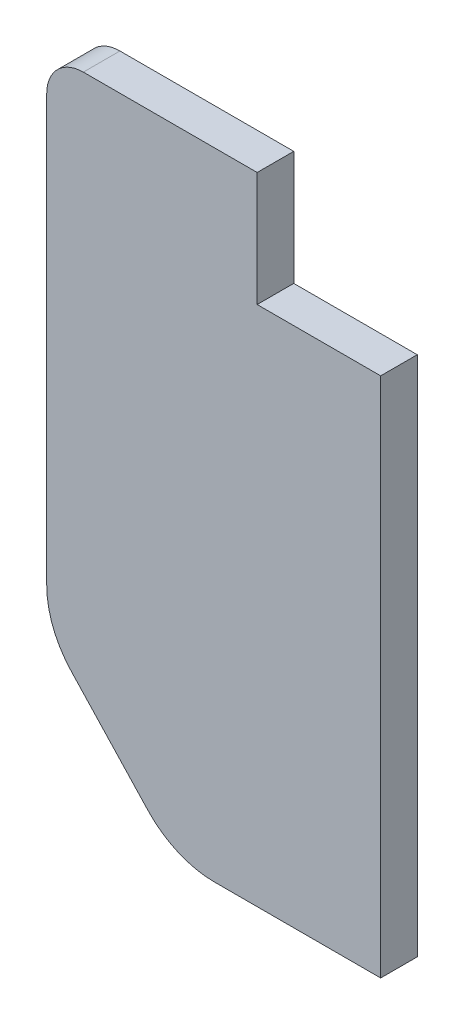
SolidWorks part; units mm, degrees
material "Q355"
ref_plane "前视基准面" through (0, 0, 0) normal (0, 0, 1) x (1, 0, 0)
ref_plane "上视基准面" through (0, 0, 0) normal (0, 1, 0) x (1, 0, 0)
ref_plane "右视基准面" through (0, 0, 0) normal (1, 0, 0) x (0, 0, -1)
sketch "草图1" plane through (0, 0, 0) normal (0, 0, 1) x (1, 0, 0)
  line L6 (0, 0) -> (0, 114)
  line L7 (0, 114) -> (-27, 114)
  line L8 (-27, 114) -> (-27, 139)
  line L9 (-27, 139) -> (-73, 139)
  line L10 (-73, 139) -> (-73, 30)
  line L11 (-73, 30) -> (-45, 0)
  line L12 (-45, 0) -> (0, 0)
  dimension "D1" = 139
  dimension "D2" = 73
  dimension "D3" = 27
  dimension "D4" = 25
  dimension "D5" = 45
  dimension "D6" = 30
extrude "凸台-拉伸1" add sketch "草图1" along normal blind 8
fillet "圆角1" radius 8 1 edges at (-73, 139, 4)
fillet "圆角2" radius 20 2 edges at (-45, 0, 4) (-73, 30, 4)
